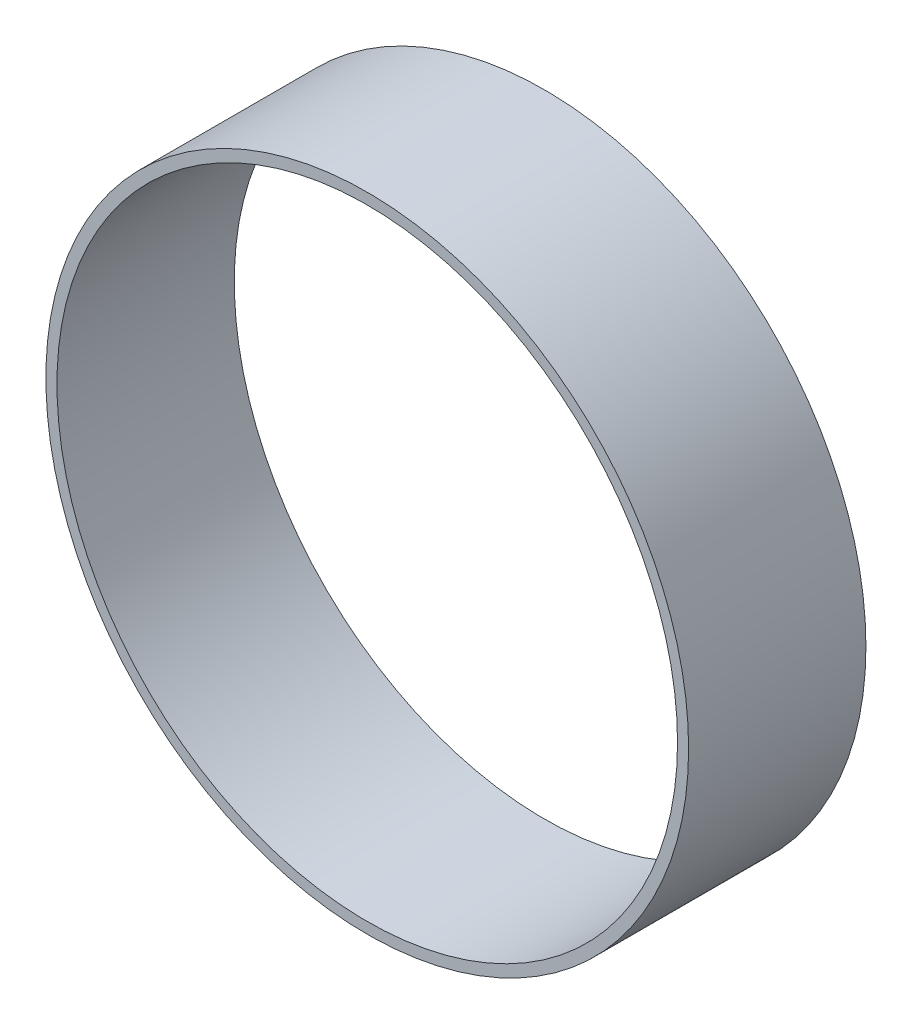
SolidWorks part; units mm, degrees
material "Molybdenum"
ref_plane "Front Plane" through (0, 0, 0) normal (0, 0, 1) x (1, 0, 0)
ref_plane "Top Plane" through (0, 0, 0) normal (0, 1, 0) x (1, 0, 0)
ref_plane "Right Plane" through (0, 0, 0) normal (1, 0, 0) x (0, 0, -1)
sketch "Sketch1" plane through (0, 0, 0) normal (0, 0, 1) x (1, 0, 0)
  circle A0 centre (0, 0) radius 72.5
  circle A1 centre (0, 0) radius 70
  dimension "D1" = 140
  dimension "D2" = 145
extrude "Boss-Extrude1" add sketch "Sketch1" along normal blind 40
